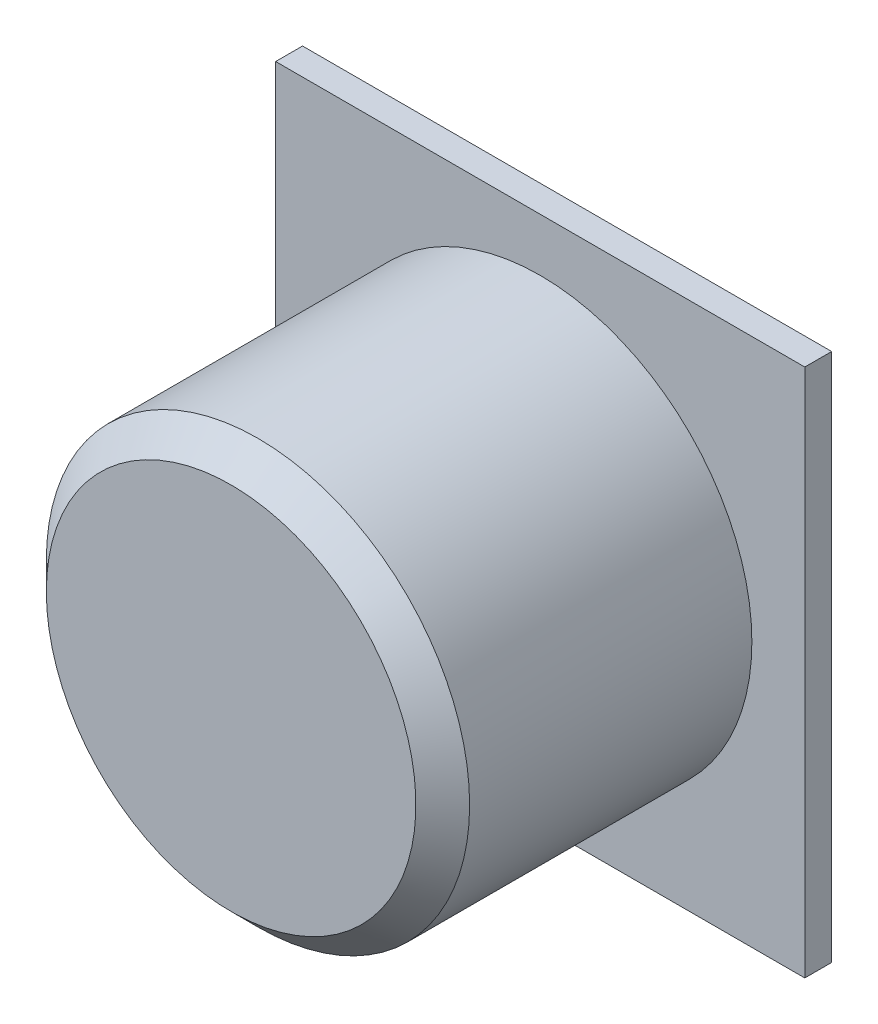
SolidWorks part; units mm, degrees
ref_plane "Front Plane" through (0, 0, 0) normal (0, 0, 1) x (1, 0, 0)
ref_plane "Top Plane" through (0, 0, 0) normal (0, 1, 0) x (1, 0, 0)
ref_plane "Right Plane" through (0, 0, 0) normal (1, 0, 0) x (0, 0, -1)
sketch "Sketch1" plane through (0, 0, 0) normal (0, 0, 1) x (1, 0, 0)
  line L1 (50, -50) -> (-50, -50)
  line L2 (50, -50) -> (50, 50)
  line L3 (50, 50) -> (-50, 50)
  line L4 (-50, -50) -> (-50, 50)
  line L5 (50, -50) -> (-50, 50) construction
  line L6 (50, 50) -> (-50, -50) construction
  point P0 (0, 0)
  dimension "D1" = 100
  dimension "D2" = 100
extrude "Boss-Extrude1" add sketch "Sketch1" along normal blind 5.08
sketch "Sketch2" plane through (0, 0, 0) normal (0, 0, 1) x (1, 0, 0)
  circle A0 centre (0, 0) radius 40
  dimension "D1" = 80
extrude "Boss-Extrude2" add sketch "Sketch2" along normal blind 63.5
chamfer "Chamfer1" distance 5.08 angle 45 1 edges at (40, 0, 63.5)
